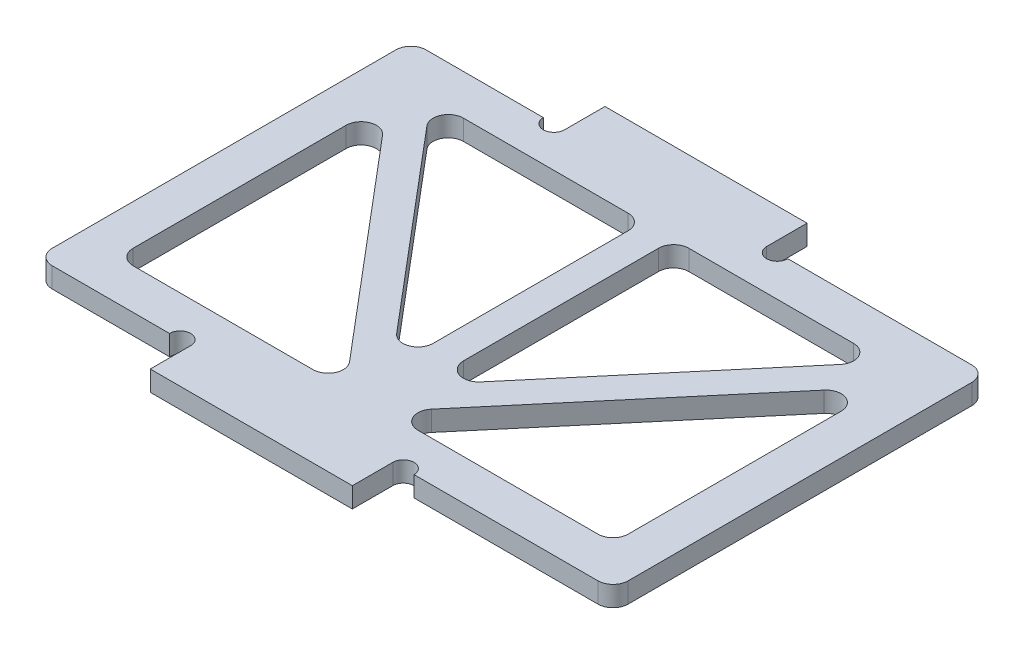
SolidWorks part; units mm, degrees
material "Thornel Mat VMA"
ref_plane "前视基准面" through (0, 0, 0) normal (0, 0, 1) x (1, 0, 0)
ref_plane "上视基准面" through (0, 0, 0) normal (0, 1, 0) x (1, 0, 0)
ref_plane "右视基准面" through (0, 0, 0) normal (1, 0, 0) x (0, 0, -1)
sketch "草图1" plane through (0, 0, 0) normal (0, 1, 0) x (1, 0, 0)
  line L1 (-28.5, -18.5) -> (28.5, -18.5)
  line L2 (-28.5, -18.5) -> (-28.5, 18.5)
  line L3 (-28.5, 18.5) -> (28.5, 18.5)
  line L4 (28.5, -18.5) -> (28.5, 18.5)
  line L5 (-28.5, -18.5) -> (28.5, 18.5) construction
  line L6 (-28.5, 18.5) -> (28.5, -18.5) construction
  point P0 (0, 0)
  dimension "D1" = 57
  dimension "D2" = 37
extrude "凸台-拉伸1" add sketch "草图1" along normal blind 2
sketch "草图2" plane through (0, 0, 18.5) normal (0, 0, 1) x (1, 0, 0)
  line L0 (6.7, 0) -> (6.7, 2) construction
  line L1 (-13.3, 2) -> (-13.3, 0) construction
  line L2 (6.7, 0) -> (6.7, 2)
  line L3 (-13.3, 2) -> (-13.3, 0)
  line L4 (-13.3, 2) -> (6.7, 2)
  line L5 (-13.3, 0) -> (6.7, 0)
extrude "凸台-拉伸2" add sketch "草图2" along normal blind 4
mirror "镜向1" about plane through (0, 0, 0) normal (0, 0, 1) of "凸台-拉伸2"
sketch "草图3" plane through (0, 2, 0) normal (0, 1, 0) x (1, 0, 0)
  line L0 (28.5, 18.5) -> (6.7, 18.5) construction
  line L1 (-13.3, 18.5) -> (-28.5, 18.5) construction
  line L2 (-28.5, -18.5) -> (-13.3, -18.5) construction
  line L3 (6.7, -18.5) -> (28.5, -18.5) construction
  circle A0 centre (7.75, 18.5) radius 1.05
  circle A1 centre (-14.35, 18.5) radius 1.05
  circle A2 centre (-14.35, -18.5) radius 1.05
  circle A3 centre (7.75, -18.5) radius 1.05
  dimension "D1" = 2.1
extrude "切除-拉伸1" cut sketch "草图3" against normal blind 4
sketch "草图4" plane through (0, 2, 0) normal (0, 1, 0) x (1, 0, 0)
  line L0 (28.5, -18.5) -> (28.5, 18.5) construction
  line L1 (-24.5, -14.5) -> (24.5, -14.5)
  line L2 (-24.5, -14.5) -> (-24.5, 14.5)
  line L3 (-24.5, 14.5) -> (24.5, 14.5)
  line L4 (24.5, -14.5) -> (24.5, 14.5)
  line L5 (0, 14.5) -> (0, -14.5) construction
  line L6 (-24.5, 0) -> (24.5, 0) construction
  line L7 (28.5, 18.5) -> (8.8, 18.5) construction
  line L8 (-24.5, 14.5) -> (0, -14.5) construction
  line L9 (0, -14.5) -> (24.5, 14.5) construction
  line L10 (1.1458, -15.468) -> (25.6458, 13.532)
  line L11 (-1.5, 14.5) -> (-1.5, -14.5)
  line L12 (-25.6458, 13.532) -> (-1.1458, -15.468)
  line L13 (-1.1458, -13.532) -> (23.3542, 15.468)
  line L14 (1.5, 14.5) -> (1.5, -14.5)
  line L15 (-23.3542, 15.468) -> (1.1458, -13.532)
  arc A0 (1.1458, -15.468) -> (-1.1458, -13.532) centre (0, -14.5) cw
  arc A1 (25.6458, 13.532) -> (23.3542, 15.468) centre (24.5, 14.5) ccw
  arc A2 (-1.5, 14.5) -> (1.5, 14.5) centre (0, 14.5) cw
  arc A3 (-1.5, -14.5) -> (1.5, -14.5) centre (0, -14.5) ccw
  arc A4 (-25.6458, 13.532) -> (-23.3542, 15.468) centre (-24.5, 14.5) cw
  arc A5 (-1.1458, -15.468) -> (1.1458, -13.532) centre (0, -14.5) ccw
  point P0 (0, 0)
  dimension "D1" = 4
  dimension "D2" = 4
  dimension "D3" = 1.5
  dimension "D4" = 1.5
extrude "切除-拉伸2" cut sketch "草图4" against normal blind 10 contours L12 L2 L1 | L3 L15 L11 | L3 L14 L13 | L10 L1 L4
fillet "圆角1" radius 1.5 16 edges at (-28.5, 1, -18.5) (28.5, 1, -18.5) (28.5, 1, 18.5) (-28.5, 1, 18.5) (-1.5, 1, 10.4002) (-22.5364, 1, -14.5) (-1.5, 1, -14.5) (1.5, 1, 10.4002) (1.5, 1, -14.5) (22.5364, 1, -14.5) (24.5, 1, 14.5) (1.9636, 1, 14.5) (24.5, 1, -12.1757) (-24.5, 1, -12.1757) (-1.9636, 1, 14.5) (-24.5, 1, 14.5)
